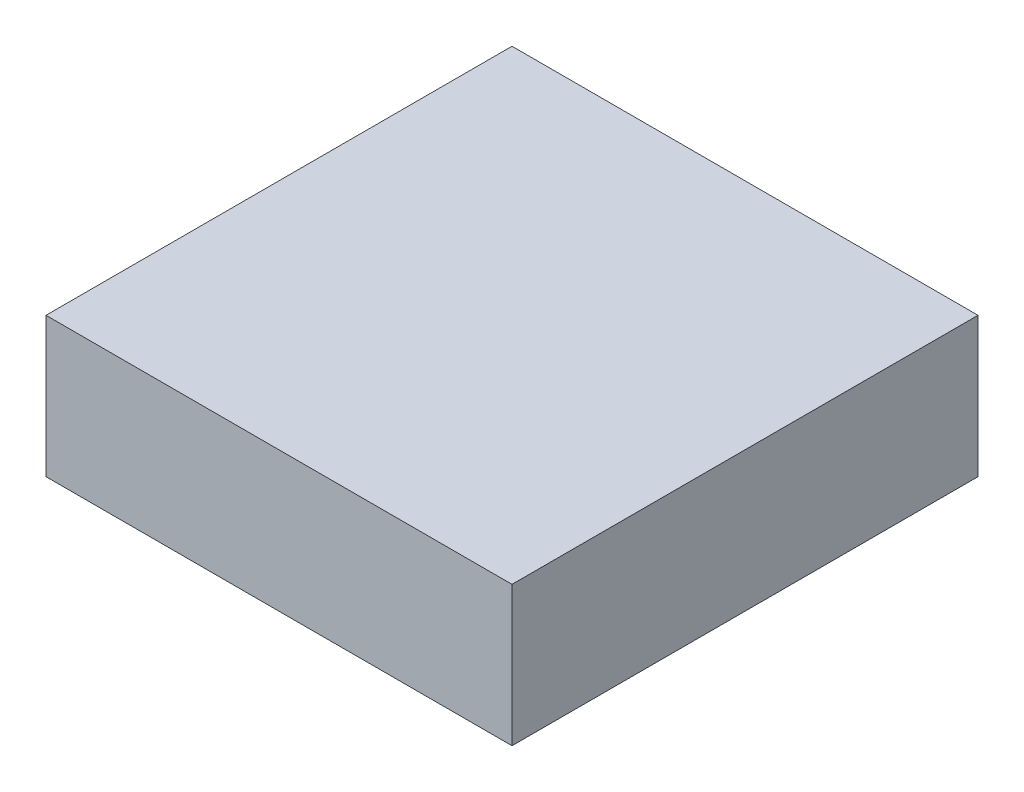
SolidWorks part; units mm, degrees
ref_plane "前视基准面" through (0, 0, 0) normal (0, 0, 1) x (1, 0, 0)
ref_plane "上视基准面" through (0, 0, 0) normal (0, 1, 0) x (1, 0, 0)
ref_plane "右视基准面" through (0, 0, 0) normal (1, 0, 0) x (0, 0, -1)
sketch "草图1" plane through (0, 0, 0) normal (0, 1, 0) x (1, 0, 0)
  line L1 (-30, -30) -> (30, -30)
  line L2 (-30, -30) -> (-30, 30)
  line L3 (-30, 30) -> (30, 30)
  line L4 (30, -30) -> (30, 30)
  line L5 (0, 30) -> (0, -30) construction
  line L6 (-30, 0) -> (30, 0) construction
  point P0 (0, 0)
  dimension "D1" = 60
  dimension "D2" = 60
extrude "凸台-拉伸1" add sketch "草图1" along normal blind 18
